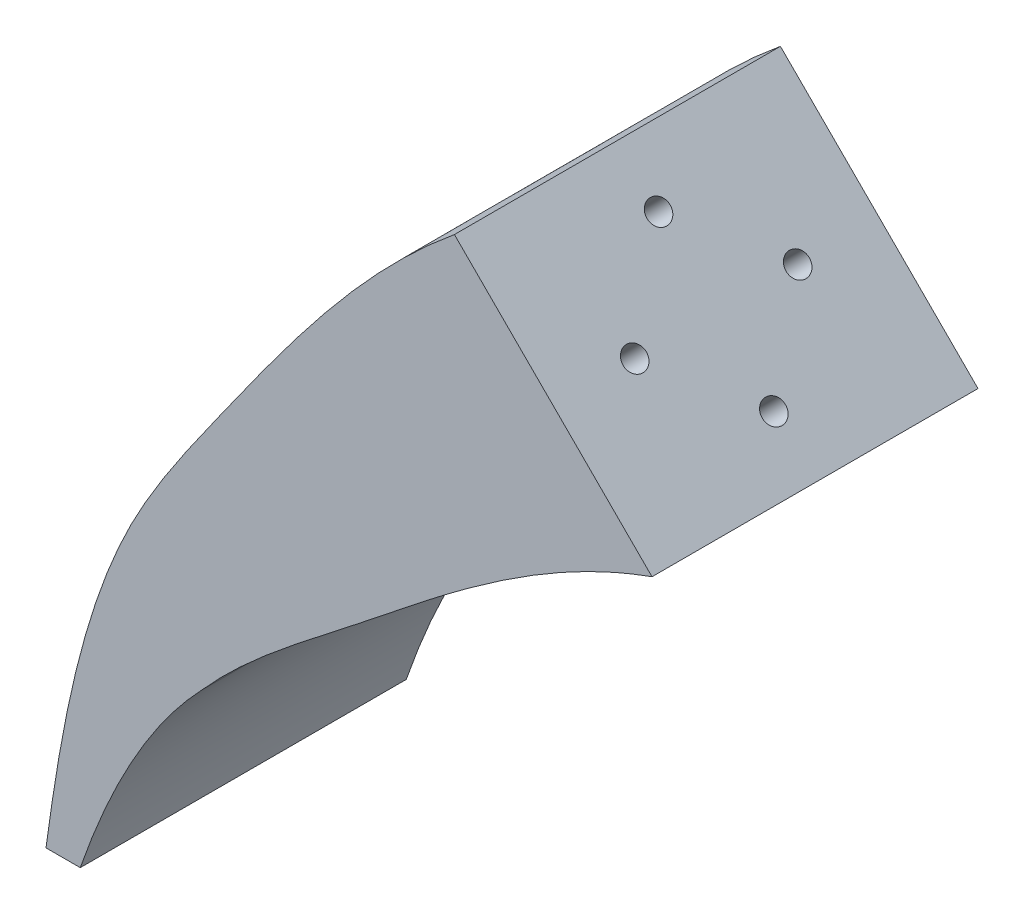
SolidWorks part; units mm, degrees
material "ABS"
ref_plane "Front Plane" through (0, 0, 0) normal (0, 0, 1) x (1, 0, 0)
ref_plane "Top Plane" through (0, 0, 0) normal (0, 1, 0) x (1, 0, 0)
ref_plane "Right Plane" through (0, 0, 0) normal (1, 0, 0) x (0, 0, -1)
sketch "Sketch1" plane through (0, 0, 0) normal (0, 0, 1) x (1, 0, 0)
  line L0 (2.0914, 20.6619) -> (19.062, 3.6913)
  line L1 (-32.9879, -42.5021) -> (-30.0455, -42.5021)
  spline S0 degree 3 poles (2.0914, 20.6619) (-6.1537, 13.9028) (-14.8845, 1.6137) (-29.2039, -18.6426) (-31.7282, -33.2087) (-32.9879, -42.5021) knots 0 0 0 0 0.426775 0.611805 1 1 1 1
  spline S1 degree 3 poles (19.062, 3.6913) (12.0226, 1.1814) (3.6067, -4.5029) (-8.7685, -14.5784) (-15.7103, -19.6509) (-19.6349, -24.0985) knots 0 0 0 0 0.463104 0.631301 1 1 1 1
  spline S2 degree 2 poles (-19.6349, -24.0985) (-25.9696, -30.7373) (-30.0455, -42.5021) knots 0 0 0 1 1 1
  dimension "D1" = 24
extrude "Boss-Extrude1" add sketch "Sketch1" along normal blind 28
sketch "Sketch2" plane through (11.3766, 11.3766, 0) normal (0.7071, 0.7071, 0) x (0, 0, -1)
  line L1 (-28, 13.1313) -> (0, 13.1313) construction
  line L2 (-28, -10.8687) -> (0, -10.8687) construction
  circle A0 centre (-7, 1.1313) radius 1
  circle A1 centre (-14, 8.1313) radius 1
  circle A2 centre (-14, -5.8687) radius 1
  circle A3 centre (-21, 1.1313) radius 1
  dimension "D1" = 1
  dimension "D2" = 2
  dimension "D3" = 1
  dimension "D5" = 12
  dimension "D6" = 5
  dimension "D7" = 5
extrude "Cut-Extrude1" cut sketch "Sketch2" against normal blind 8
